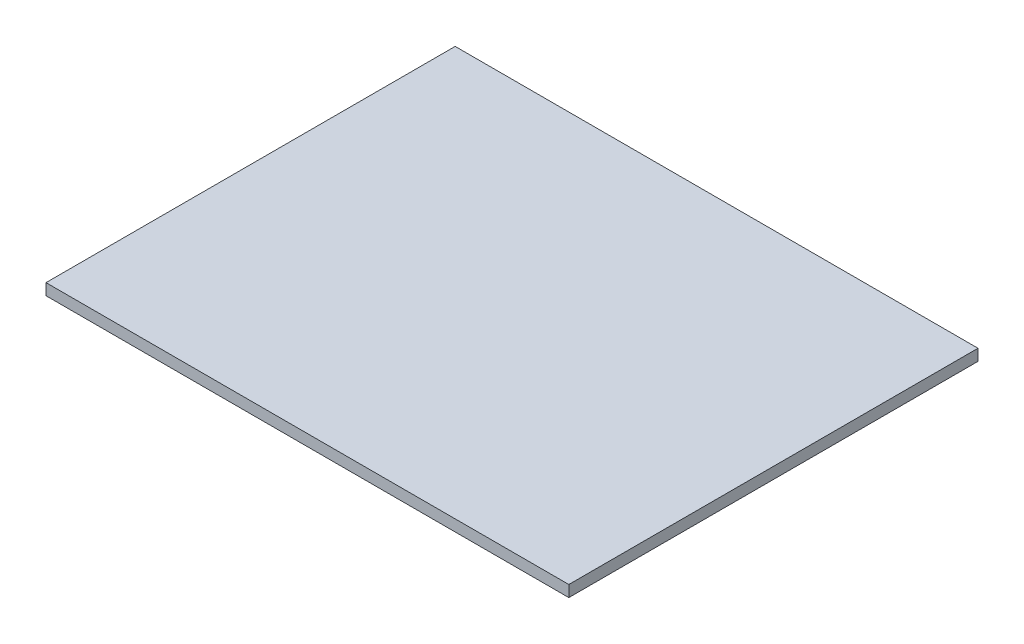
SolidWorks part; units mm, degrees
ref_plane "Front Plane" through (0, 0, 0) normal (0, 0, 1) x (1, 0, 0)
ref_plane "Top Plane" through (0, 0, 0) normal (0, 1, 0) x (1, 0, 0)
ref_plane "Right Plane" through (0, 0, 0) normal (1, 0, 0) x (0, 0, -1)
sketch "Sketch1" plane through (0, 0, 0) normal (0, 1, 0) x (1, 0, 0)
  line L0 (-292.1, -457.2) -> (-292.1, 0) construction
  line L1 (292.1, -457.2) -> (-292.1, -457.2)
  line L2 (292.1, -457.2) -> (292.1, 0)
  line L3 (292.1, 0) -> (-292.1, 0)
  line L4 (-292.1, -457.2) -> (-292.1, 0)
  line L5 (292.1, -457.2) -> (-292.1, 0) construction
  line L6 (292.1, 0) -> (-292.1, -457.2) construction
  line L7 (292.1, -457.2) -> (304.8, -457.2) construction
  point P0 (0, -228.6)
extrude "Boss-Extrude1" add sketch "Sketch1" along normal blind 12.7
